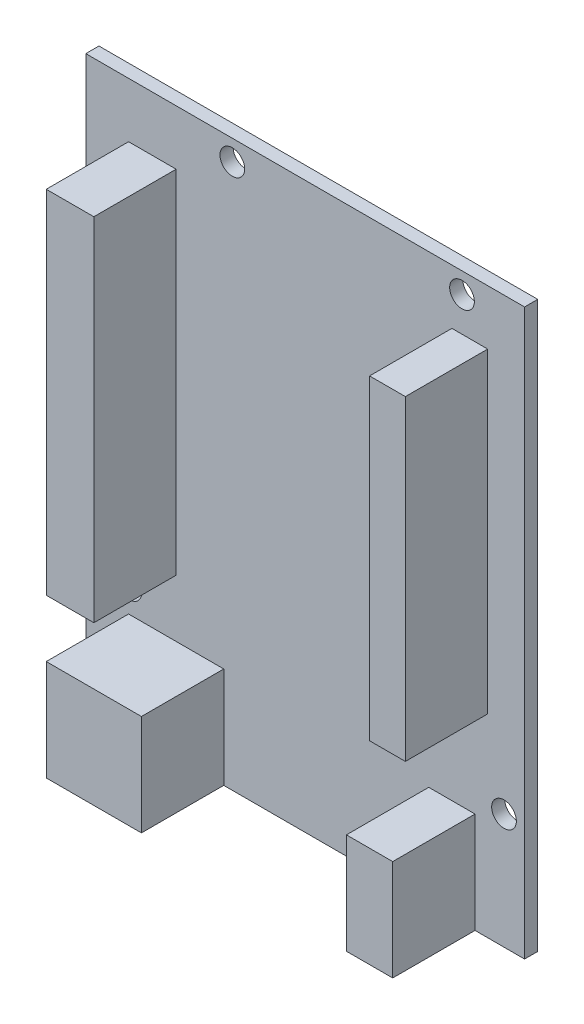
SolidWorks part; units mm, degrees
ref_plane "前视基准面" through (0, 0, 0) normal (0, 0, 1) x (1, 0, 0)
ref_plane "上视基准面" through (0, 0, 0) normal (0, 1, 0) x (1, 0, 0)
ref_plane "右视基准面" through (0, 0, 0) normal (1, 0, 0) x (0, 0, -1)
sketch "草图1" plane through (0, 0, 0) normal (0, 0, 1) x (1, 0, 0)
  line L1 (-37.7908, 53.4481) -> (15.5092, 53.4481)
  line L2 (-37.7908, 53.4481) -> (-37.7908, -15.1519)
  line L3 (-37.7908, -15.1519) -> (15.5092, -15.1519)
  line L4 (15.5092, 53.4481) -> (15.5092, -15.1519)
  circle A0 centre (-19.9908, 50.9481) radius 1.5
  circle A1 centre (7.9092, 50.9481) radius 1.5
  circle A2 centre (-32.4908, 0.1481) radius 1.5
  circle A3 centre (13.0092, -1.1519) radius 1.5
  dimension "D1" = 3
  dimension "D2" = 27.9
  dimension "D3" = 12.5
  dimension "D4" = 50.8
  dimension "D5" = 1.3
  dimension "D6" = 5.1
  dimension "D7" = 68.6
  dimension "D8" = 53.3
  dimension "D9" = 14
  dimension "D10" = 2.5
extrude "凸台-拉伸1" add sketch "草图1" along normal blind 1.6
sketch "草图2" plane through (0, 0, 1.6) normal (0, 0, 1) x (1, 0, 0)
  line L0 (-37.7908, -15.1519) -> (15.5092, -15.1519) construction
  line L1 (-32.5922, -15.1519) -> (-21.031, -15.1519)
  line L2 (-32.5922, -15.1519) -> (-32.5922, -2.9036)
  line L3 (-32.5922, -2.9036) -> (-21.031, -2.9036)
  line L4 (-21.031, -15.1519) -> (-21.031, -2.9036)
  line L6 (3.87, -15.1519) -> (9.4922, -15.1519)
  line L7 (3.87, -15.1519) -> (3.87, -2.9036)
  line L8 (3.87, -2.9036) -> (9.4922, -2.9036)
  line L9 (9.4922, -15.1519) -> (9.4922, -2.9036)
  line L10 (-32.5922, 46.7786) -> (-26.8116, 46.7786)
  line L11 (-32.5922, 46.7786) -> (-32.5922, 4.0677)
  line L12 (-32.5922, 4.0677) -> (-26.8116, 4.0677)
  line L13 (-26.8116, 46.7786) -> (-26.8116, 4.0677)
  line L14 (6.6811, 46.7786) -> (11.0292, 46.7786)
  line L15 (6.6811, 46.7786) -> (6.6811, 8.3984)
  line L16 (6.6811, 8.3984) -> (11.0292, 8.3984)
  line L17 (11.0292, 46.7786) -> (11.0292, 8.3984)
extrude "凸台-拉伸2" add sketch "草图2" along normal blind 10
